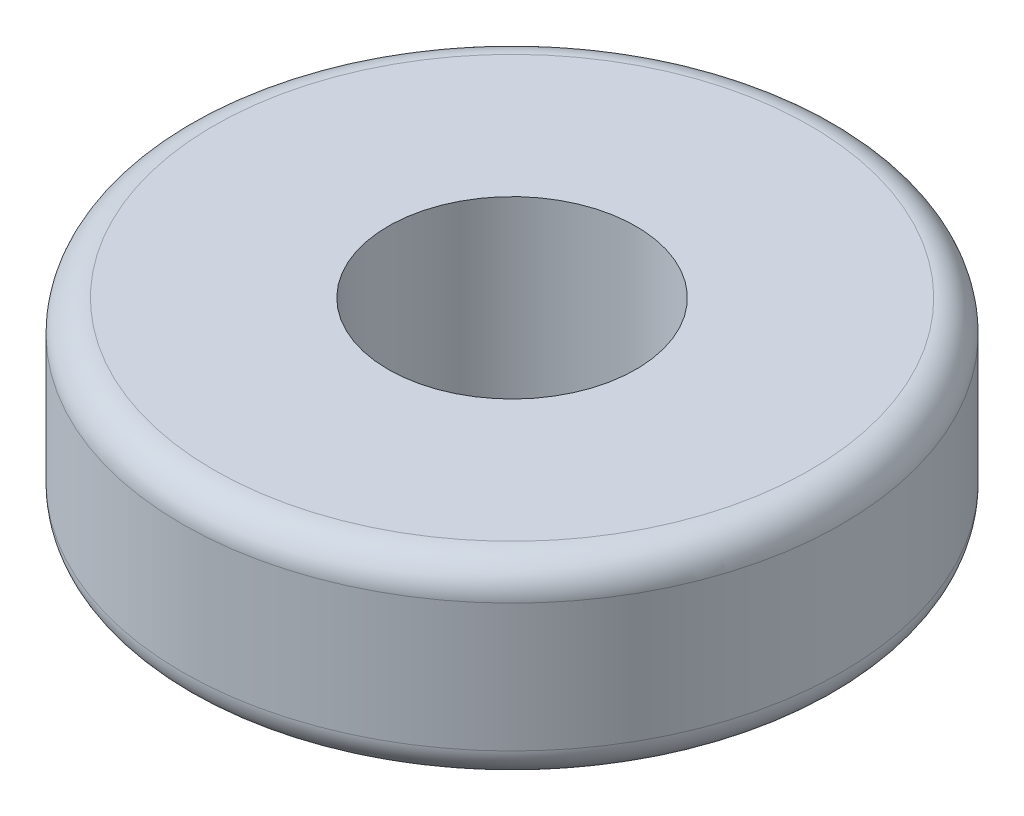
SolidWorks part; units mm, degrees
ref_plane "Front Plane" through (0, 0, 0) normal (0, 0, 1) x (1, 0, 0)
ref_plane "Top Plane" through (0, 0, 0) normal (0, 1, 0) x (1, 0, 0)
ref_plane "Right Plane" through (0, 0, 0) normal (1, 0, 0) x (0, 0, -1)
sketch "Sketch2" plane through (0, 0, 0) normal (0, 1, 0) x (1, 0, 0)
  circle A0 centre (0, 0) radius 10.5
  circle A1 centre (0, 0) radius 3.95
  dimension "D1" = 21
  dimension "D2" = 7.9
extrude "Boss-Extrude1" add sketch "Sketch2" along normal blind 6.08
fillet "Fillet1" radius 1 2 edges at (0, 0, 10.5) (0, 6.08, 10.5)
